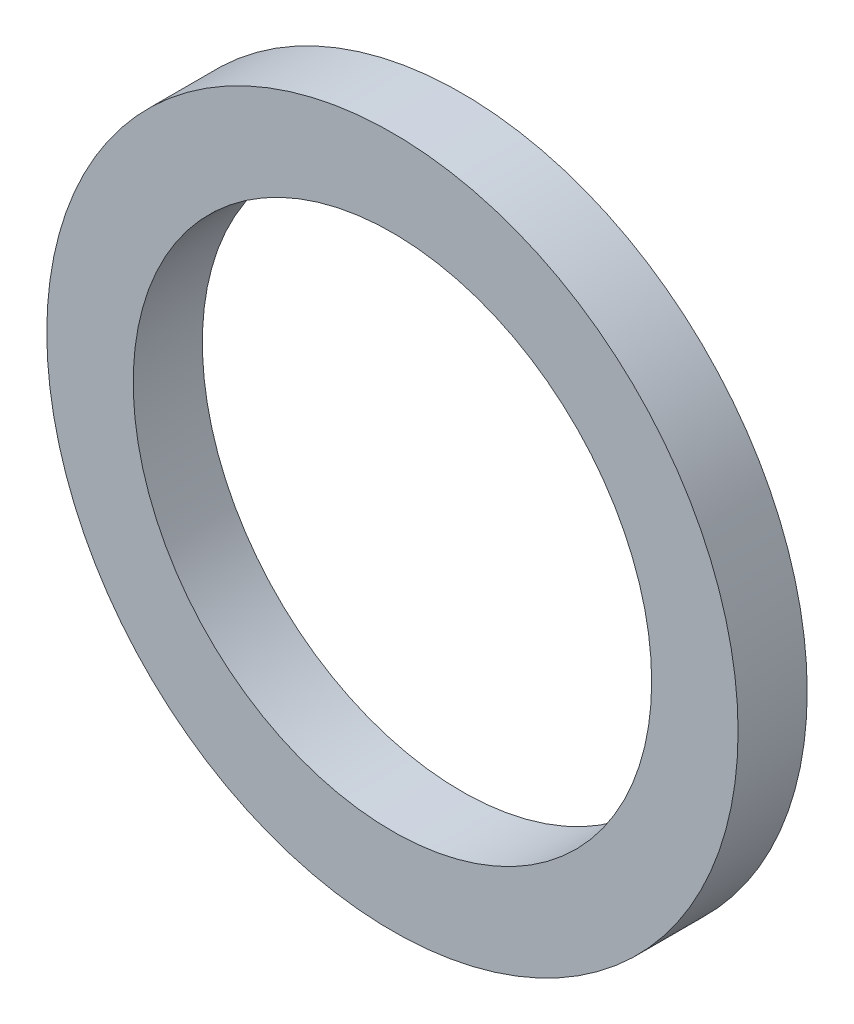
SolidWorks part; units mm, degrees
ref_plane "Přední rovina" through (0, 0, 0) normal (0, 0, 1) x (1, 0, 0)
ref_plane "Horní rovina" through (0, 0, 0) normal (0, 1, 0) x (1, 0, 0)
ref_plane "Pravá rovina" through (0, 0, 0) normal (1, 0, 0) x (0, 0, -1)
sketch "Skica1" plane through (0, 0, 0) normal (0, 0, 1) x (1, 0, 0)
  circle A0 centre (0, 0) radius 3
  circle A1 centre (0, 0) radius 4
  dimension "D1" = 6
  dimension "D2" = 1
extrude "Přidat vysunutím1" add sketch "Skica1" along normal blind 0.8
